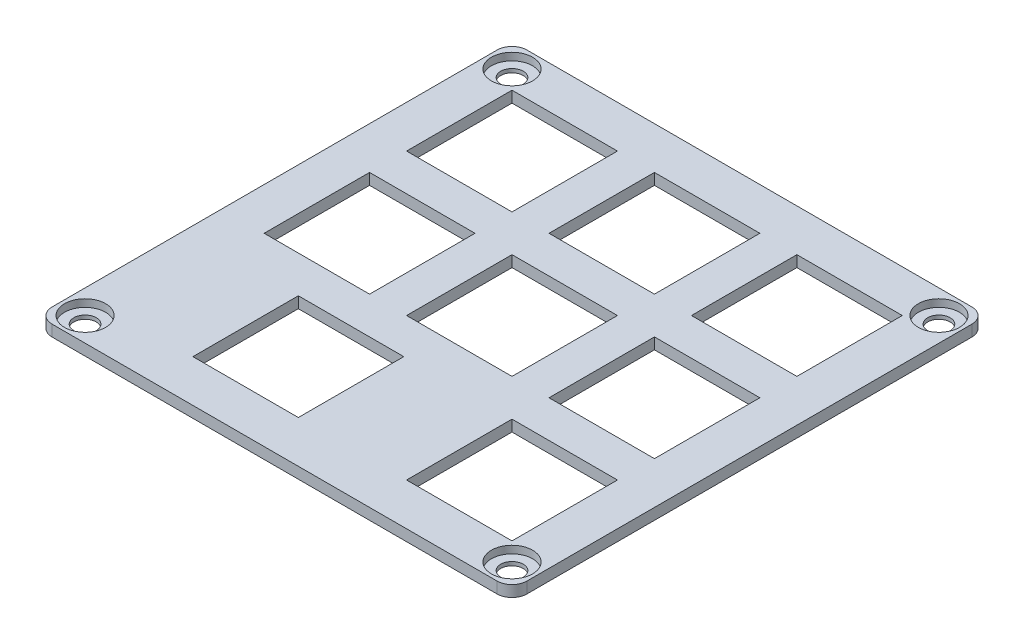
SolidWorks part; units mm, degrees
ref_plane "Front Plane" through (0, 0, 0) normal (0, 0, 1) x (1, 0, 0)
ref_plane "Top Plane" through (0, 0, 0) normal (0, 1, 0) x (1, 0, 0)
ref_plane "Right Plane" through (0, 0, 0) normal (1, 0, 0) x (0, 0, -1)
sketch "Sketch1" plane through (0, 0, 0) normal (0, 1, 0) x (1, 0, 0)
  line L1 (0, 0) -> (63.5, 0)
  line L2 (0, 0) -> (0, 63.5)
  line L3 (0, 63.5) -> (63.5, 63.5)
  line L4 (63.5, 0) -> (63.5, 63.5)
  dimension "D1" = 63.5
extrude "Boss-Extrude1" add sketch "Sketch1" along normal blind 1.5
sketch "Sketch2" plane through (0, 1.5, 0) normal (0, 1, 0) x (1, 0, 0)
  line L0 (31.75, 63.5) -> (31.75, 0) construction
  line L1 (5.65, 57.85) -> (19.75, 57.85)
  line L2 (5.65, 57.85) -> (5.65, 43.75)
  line L3 (5.65, 43.75) -> (19.75, 43.75)
  line L4 (19.75, 57.85) -> (19.75, 43.75)
  line L5 (24.7, 57.85) -> (38.8, 57.85)
  line L6 (24.7, 57.85) -> (24.7, 43.75)
  line L7 (24.7, 43.75) -> (38.8, 43.75)
  line L8 (38.8, 57.85) -> (38.8, 43.75)
  line L9 (43.75, 57.85) -> (57.85, 57.85)
  line L10 (43.75, 57.85) -> (43.75, 43.75)
  line L11 (43.75, 43.75) -> (57.85, 43.75)
  line L12 (57.85, 57.85) -> (57.85, 43.75)
  line L13 (5.65, 38.8) -> (19.75, 38.8)
  line L14 (5.65, 38.8) -> (5.65, 24.7)
  line L15 (5.65, 24.7) -> (19.75, 24.7)
  line L16 (19.75, 38.8) -> (19.75, 24.7)
  line L17 (24.7, 38.8) -> (38.8, 38.8)
  line L18 (24.7, 38.8) -> (24.7, 24.7)
  line L19 (24.7, 24.7) -> (38.8, 24.7)
  line L20 (38.8, 38.8) -> (38.8, 24.7)
  line L21 (43.75, 38.8) -> (57.85, 38.8)
  line L22 (43.75, 38.8) -> (43.75, 24.7)
  line L23 (43.75, 24.7) -> (57.85, 24.7)
  line L24 (57.85, 38.8) -> (57.85, 24.7)
  line L25 (15.175, 19.75) -> (29.275, 19.75)
  line L26 (15.175, 19.75) -> (15.175, 5.65)
  line L27 (15.175, 5.65) -> (29.275, 5.65)
  line L28 (29.275, 19.75) -> (29.275, 5.65)
  line L29 (43.75, 19.75) -> (57.85, 19.75)
  line L30 (43.75, 19.75) -> (43.75, 5.65)
  line L31 (43.75, 5.65) -> (57.85, 5.65)
  line L32 (57.85, 19.75) -> (57.85, 5.65)
  line L33 (63.5, 63.5) -> (0, 63.5) construction
  line L34 (0, 0) -> (63.5, 0) construction
  line L35 (0, 31.75) -> (63.5, 31.75) construction
  line L36 (0, 63.5) -> (0, 0) construction
  line L37 (63.5, 0) -> (63.5, 63.5) construction
  line L38 (12.7, 63.5) -> (12.7, 0) construction
  line L39 (50.8, 63.5) -> (50.8, 0) construction
  line L40 (0, 50.8) -> (63.5, 50.8) construction
  line L41 (0, 12.7) -> (63.5, 12.7) construction
  line L42 (22.225, 63.5) -> (22.225, 0) construction
  circle A4 centre (3.2, 60.3) radius 1.5
  circle A5 centre (60.3, 60.3) radius 1.5
  circle A6 centre (60.3, 3.2) radius 1.5
  circle A7 centre (3.2, 3.2) radius 1.5
  point P52 (12.7, 43.75)
  point P53 (19.75, 50.8)
  point P54 (31.75, 43.75)
  point P55 (38.8, 50.8)
  point P56 (50.8, 43.75)
  point P57 (57.85, 50.8)
  point P58 (12.7, 24.7)
  point P59 (19.75, 31.75)
  point P60 (31.75, 24.7)
  point P61 (38.8, 31.75)
  point P62 (50.8, 24.7)
  point P63 (57.85, 31.75)
  point P64 (50.8, 5.65)
  point P65 (57.85, 12.7)
  point P66 (29.275, 12.7)
  point P69 (22.225, 19.75)
  dimension "D7" = 3
  dimension "D8" = 3.2
  dimension "D1" = 14.1
  dimension "D2" = 19.05
  dimension "D3" = 19.05
  dimension "D4" = 19.05
  dimension "D5" = 19.05
  dimension "D6" = 9.525
  dimension "D9" = 3.2
  dimension "D10" = 3.2
  dimension "D11" = 3.2
  dimension "D12" = 3.2
  dimension "D13" = 3.2
  dimension "D14" = 3.2
  dimension "D15" = 3.2
extrude "Cut-Extrude1" cut sketch "Sketch2" against normal through all
sketch "Sketch4" plane through (0, 1.5, 0) normal (0, 1, 0) x (1, 0, 0)
  circle A5 centre (3.2, 60.3) radius 2.75
  circle A6 centre (60.3, 60.3) radius 2.75
  circle A7 centre (60.3, 3.2) radius 2.75
  circle A8 centre (3.2, 3.2) radius 2.75
  dimension "D1" = 5.5
  dimension "D2" = 5.5
  dimension "D3" = 5.5
  dimension "D4" = 5.5
extrude "Cut-Extrude2" cut sketch "Sketch4" against normal blind 1
fillet "Fillet1" radius 2 4 edges at (63.5, 0.75, -63.5) (0, 0.75, -63.5) (0, 0.75, 0) (63.5, 0.75, 0)
